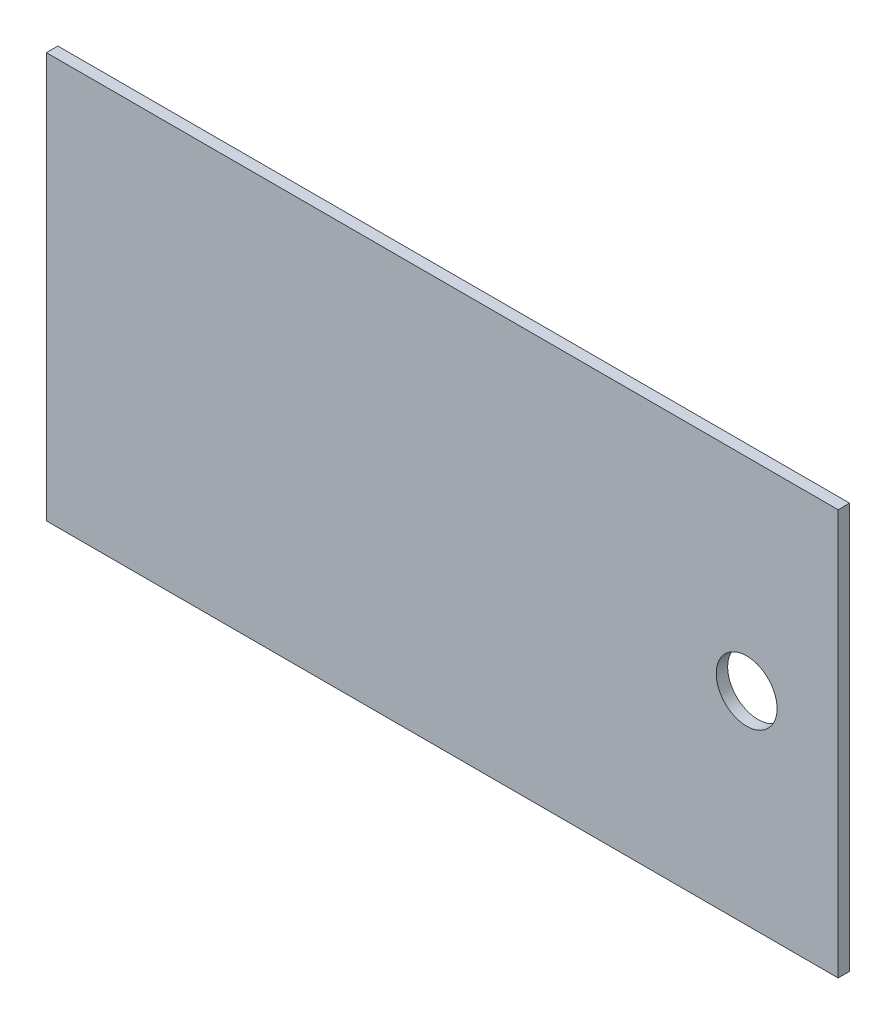
SolidWorks part; units mm, degrees
ref_plane "Front Plane" through (0, 0, 0) normal (0, 0, 1) x (1, 0, 0)
ref_plane "Top Plane" through (0, 0, 0) normal (0, 1, 0) x (1, 0, 0)
ref_plane "Right Plane" through (0, 0, 0) normal (1, 0, 0) x (0, 0, -1)
sketch "Sketch3" plane through (0, 0, 0) normal (0, 0, 1) x (1, 0, 0)
  line L1 (-161.3975, 26.2375) -> (11.6025, 26.2375)
  line L2 (-161.3975, 26.2375) -> (-161.3975, -62.3625)
  line L3 (-161.3975, -62.3625) -> (11.6025, -62.3625)
  line L4 (11.6025, 26.2375) -> (11.6025, -62.3625)
  dimension "D1" = 88.6
  dimension "D2" = 173
extrude "Boss-Extrude1" add sketch "Sketch3" along normal blind 2.5 contours L2 L1 L4 L3
sketch "Sketch4" plane through (0, 0, 2.5) normal (0, 0, 1) x (1, 0, 0)
  line L0 (-36.3975, 26.2375) -> (-36.3975, -62.3625)
  line L1 (-161.3975, 26.2375) -> (11.6025, 26.2375) construction
  line L2 (-161.3975, -62.3625) -> (11.6025, -62.3625) construction
  line L3 (11.6025, 26.2375) -> (11.6025, -62.3625) construction
  circle A0 centre (-8.3975, -18.0625) radius 6.65
  dimension "D2" = 13.3
  dimension "D3" = 20
  dimension "D1" = 48
extrude "Cut-Extrude1" cut sketch "Sketch4" against normal blind 10 contours A0
